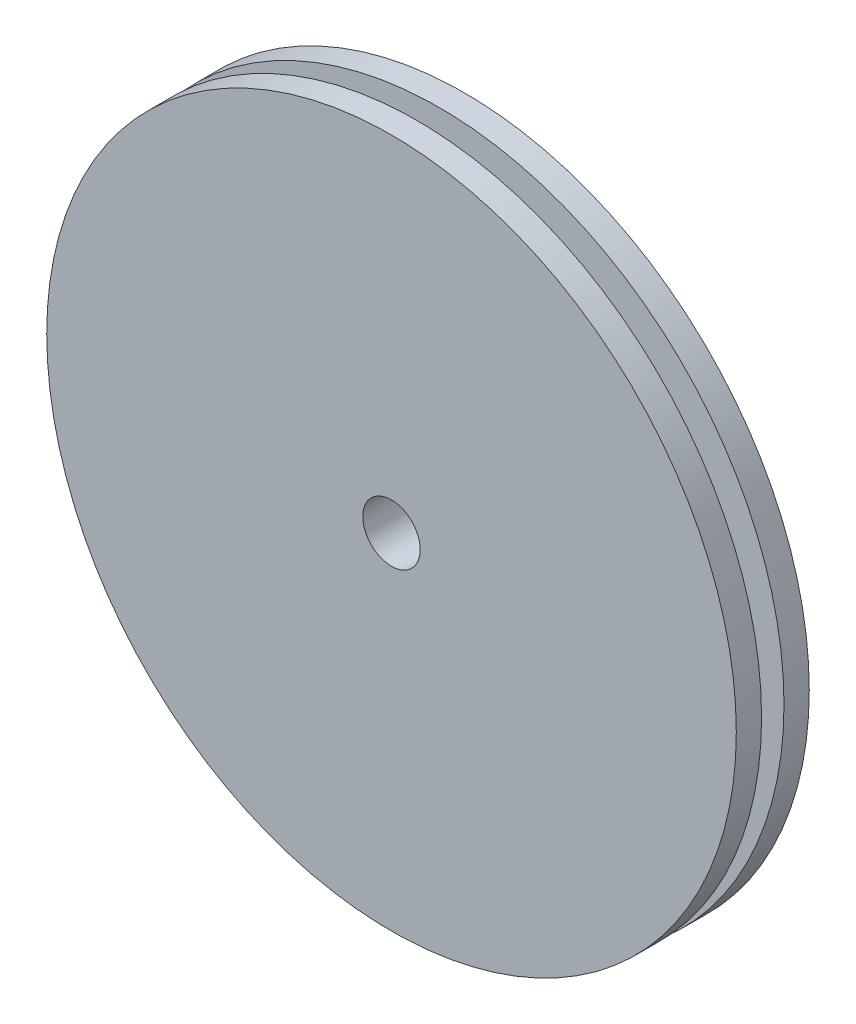
SolidWorks part; units mm, degrees
ref_plane "Front Plane" through (0, 0, 0) normal (0, 0, 1) x (1, 0, 0)
ref_plane "Top Plane" through (0, 0, 0) normal (0, 1, 0) x (1, 0, 0)
ref_plane "Right Plane" through (0, 0, 0) normal (1, 0, 0) x (0, 0, -1)
sketch "Sketch1" plane through (0, 0, 0) normal (0, 0, 1) x (1, 0, 0)
  circle A0 centre (0, 0) radius 60
  dimension "D1" = 120
extrude "Boss-Extrude2" add sketch "Sketch1" along normal blind 4.4
sketch "Sketch2" plane through (0, 0, 4.4) normal (0, 0, 1) x (1, 0, 0)
  circle A0 centre (0, 0) radius 20
  dimension "D1" = 40
extrude "Cut-Extrude1" cut sketch "Sketch2" against normal blind 20.9
sketch "Sketch3" plane through (0, 0, 4.4) normal (0, 0, 1) x (1, 0, 0)
  circle A0 centre (0, 0) radius 48.4681
extrude "Boss-Extrude3" add sketch "Sketch3" along normal blind 3.9
sketch "Sketch4" plane through (0, 0, 8.3) normal (0, 0, 1) x (1, 0, 0)
  circle A0 centre (0, 0) radius 60
  dimension "D1" = 120
extrude "Boss-Extrude4" add sketch "Sketch4" along normal blind 4.4
sketch "Sketch5" plane through (0, 0, 4.4) normal (0, 0, -1) x (-1, 0, 0)
  circle A0 centre (0, 0) radius 3
  circle A1 centre (0, 0) radius 20
  dimension "D1" = 6
extrude "Boss-Extrude5" add sketch "Sketch5" along normal blind 4
sketch "Sketch7" plane through (0, 0, 4.4) normal (0, 0, -1) x (-1, 0, 0)
  circle A0 centre (0, 0) radius 5
extrude "Cut-Extrude4" cut sketch "Sketch7" against normal blind 16
